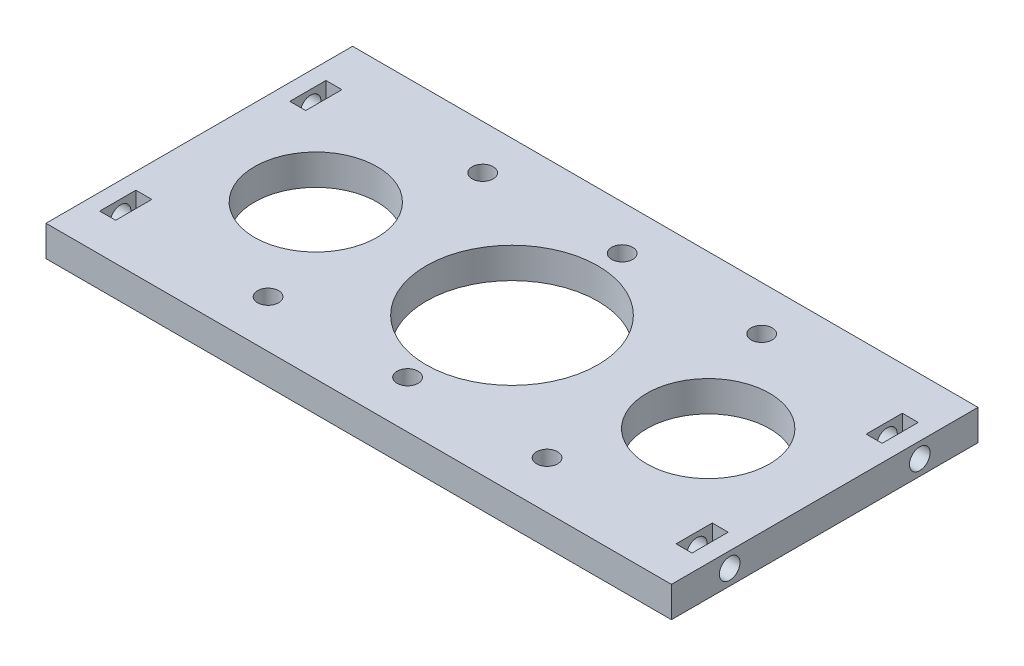
SolidWorks part; units mm, degrees
material "ABS"
ref_plane "Front Plane" through (0, 0, 0) normal (0, 0, 1) x (1, 0, 0)
ref_plane "Top Plane" through (0, 0, 0) normal (0, 1, 0) x (1, 0, 0)
ref_plane "Right Plane" through (0, 0, 0) normal (1, 0, 0) x (0, 0, -1)
sketch "Agujeros" plane through (0, 0, 0) normal (0, 1, 0) x (1, 0, 0)
  line L0 (48.0256, -13.2344) -> (45.4256, -13.2344)
  line L1 (48.0256, -13.2344) -> (48.0256, -19.1344)
  line L2 (48.0256, -19.1344) -> (45.4256, -19.1344)
  line L3 (45.4256, -13.2344) -> (45.4256, -19.1344)
  line L4 (48.0256, 17.7656) -> (45.4256, 17.7656)
  line L5 (48.0256, 17.7656) -> (48.0256, 11.8656)
  line L6 (48.0256, 11.8656) -> (45.4256, 11.8656)
  line L7 (45.4256, 17.7656) -> (45.4256, 11.8656)
  line L8 (-45.9744, -13.2344) -> (-48.5744, -13.2344)
  line L9 (-45.9744, -13.2344) -> (-45.9744, -19.1344)
  line L10 (-45.9744, -19.1344) -> (-48.5744, -19.1344)
  line L11 (-48.5744, -13.2344) -> (-48.5744, -19.1344)
  line L12 (-45.9744, 17.7656) -> (-48.5744, 17.7656)
  line L13 (-45.9744, 17.7656) -> (-45.9744, 11.8656)
  line L14 (-45.9744, 11.8656) -> (-48.5744, 11.8656)
  line L15 (-48.5744, 17.7656) -> (-48.5744, 11.8656)
  line L16 (50.7656, -25.2344) -> (-51.2344, -25.2344)
  line L17 (50.7656, -25.2344) -> (50.7656, 24.7656)
  line L18 (50.7656, 24.7656) -> (-51.2344, 24.7656)
  line L19 (-51.2344, -25.2344) -> (-51.2344, 24.7656)
  circle A6 centre (31.7656, -0.2344) radius 10
  circle A7 centre (-0.2344, -0.2344) radius 14
  circle A8 centre (-32.2344, -0.2344) radius 10
extrude "Boss-Extrude1" add sketch "Agujeros" along normal blind 5
sketch "Base" plane through (0, 5, 0) normal (0, 1, 0) x (1, 0, 0)
  circle A0 centre (0, 17.5) radius 1.72
  circle A1 centre (-22.75, 17.5) radius 1.72
  circle A2 centre (22.75, 17.5) radius 1.72
  circle A3 centre (0, -17.5) radius 1.72
  circle A4 centre (22.75, -17.5) radius 1.72
  circle A5 centre (-22.75, -17.5) radius 1.72
extrude "Cut-Extrude1" cut sketch "Base" against normal through all
sketch "Sketch4" plane through (-51.2344, 0, 0) normal (-1, 0, 0) x (0, 0, 1)
  line L0 (-24.7656, 5) -> (-24.7656, 0) construction
  line L1 (25.2344, 5) -> (25.2344, 0) construction
  circle A0 centre (-15.2656, 2.5) radius 1.68
  circle A1 centre (15.7344, 2.5) radius 1.68
  dimension "D1" = 9.5
  dimension "D2" = 9.5
extrude "Cut-Extrude2" cut sketch "Sketch4" against normal blind 20
sketch "AgujerosLaterales" plane through (50.7656, 0, 0) normal (1, 0, 0) x (0, 0, -1)
  line L0 (24.7656, 5) -> (24.7656, 0) construction
  line L1 (-25.2344, 5) -> (-25.2344, 0) construction
  circle A0 centre (-15.7344, 2.5) radius 1.68
  circle A1 centre (15.2656, 2.5) radius 1.68
  dimension "D1" = 9.5
  dimension "D2" = 9.5
extrude "Cut-Extrude3" cut sketch "AgujerosLaterales" against normal blind 20
